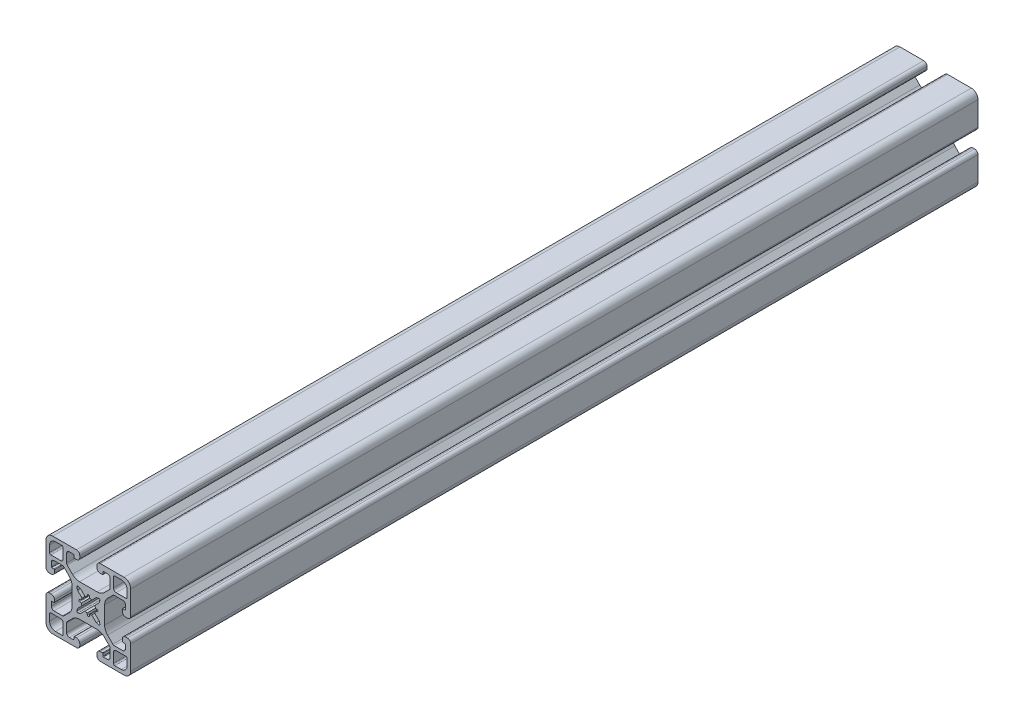
SolidWorks part; units mm, degrees
other "Extrude1"
material "6105-T5 Aluminum"
ref_plane "Front Plane" through (0, 0, 0) normal (0, 0, 1) x (1, 0, 0)
ref_plane "Top Plane" through (0, 0, 0) normal (0, 1, 0) x (1, 0, 0)
ref_plane "Right Plane" through (0, 0, 0) normal (1, 0, 0) x (0, 0, -1)
sketch "Sketch1" plane through (0, 0, 0) normal (0, 0, 1) x (1, 0, 0)
  line L0 (12.4898, -18.345) -> (15.545, -18.345)
  line L1 (11.8598, -13.1298) -> (11.8598, -17.715)
  line L2 (17.715, -11.8598) -> (13.1298, -11.8598)
  line L3 (18.345, -15.545) -> (18.345, -12.4898)
  line L4 (-18.345, -12.4898) -> (-18.345, -15.545)
  line L5 (-13.1298, -11.8598) -> (-17.715, -11.8598)
  line L6 (-11.8598, -17.715) -> (-11.8598, -13.1298)
  line L7 (-15.545, -18.345) -> (-12.4898, -18.345)
  line L8 (18.345, 12.4898) -> (18.345, 15.545)
  line L9 (13.1298, 11.8598) -> (17.715, 11.8598)
  line L10 (11.8598, 17.715) -> (11.8598, 13.1298)
  line L11 (15.545, 18.345) -> (12.4898, 18.345)
  line L12 (-12.4898, 18.345) -> (-15.545, 18.345)
  line L13 (-11.8598, 13.1298) -> (-11.8598, 17.715)
  line L14 (-17.715, 11.8598) -> (-13.1298, 11.8598)
  line L15 (-18.345, 15.545) -> (-18.345, 12.4898)
  line L16 (-5.63, 20) -> (-16.83, 20)
  line L17 (-20, 16.83) -> (-20, 5.63)
  line L18 (-18.43, 4.06) -> (-17.57, 4.06)
  line L19 (-16, 5.63) -> (-16, 6.605)
  line L20 (-16.25, 6.855) -> (-17.25, 6.855)
  line L21 (-17.5, 7.105) -> (-17.5, 9.015)
  line L22 (-16.23, 10.285) -> (-12.2162, 10.285)
  line L23 (-11.5869, 10.0243) -> (-9.0762, 7.5137)
  line L24 (-7.685, 4.1549) -> (-7.685, -4.1549)
  line L25 (-9.0762, -7.5137) -> (-11.5869, -10.0243)
  line L26 (-12.2162, -10.285) -> (-16.23, -10.285)
  line L27 (-17.5, -9.015) -> (-17.5, -7.105)
  line L28 (-17.25, -6.855) -> (-16.25, -6.855)
  line L29 (-16, -6.605) -> (-16, -5.63)
  line L30 (-17.57, -4.06) -> (-18.43, -4.06)
  line L31 (-20, -5.63) -> (-20, -16.83)
  line L32 (-16.83, -20) -> (-5.63, -20)
  line L33 (-4.06, -18.43) -> (-4.06, -17.57)
  line L34 (-5.63, -16) -> (-6.605, -16)
  line L35 (-6.855, -16.25) -> (-6.855, -17.25)
  line L36 (-7.105, -17.5) -> (-9.015, -17.5)
  line L37 (-10.285, -16.23) -> (-10.285, -12.2162)
  line L38 (-10.0243, -11.5869) -> (-7.5137, -9.0762)
  line L39 (-4.1549, -7.685) -> (4.1549, -7.685)
  line L40 (7.5137, -9.0762) -> (10.0243, -11.5869)
  line L41 (10.285, -12.2162) -> (10.285, -16.23)
  line L42 (9.015, -17.5) -> (7.105, -17.5)
  line L43 (6.855, -17.25) -> (6.855, -16.25)
  line L44 (6.605, -16) -> (5.63, -16)
  line L45 (4.06, -17.57) -> (4.06, -18.43)
  line L46 (5.63, -20) -> (16.83, -20)
  line L47 (20, -16.83) -> (20, -5.63)
  line L48 (18.43, -4.06) -> (17.57, -4.06)
  line L49 (16, -5.63) -> (16, -6.605)
  line L50 (16.25, -6.855) -> (17.25, -6.855)
  line L51 (17.5, -7.105) -> (17.5, -9.015)
  line L52 (16.23, -10.285) -> (12.2162, -10.285)
  line L53 (11.5869, -10.0243) -> (9.0762, -7.5137)
  line L54 (7.685, -4.1549) -> (7.685, 4.1549)
  line L55 (9.0762, 7.5137) -> (11.5869, 10.0243)
  line L56 (12.2162, 10.285) -> (16.23, 10.285)
  line L57 (17.5, 9.015) -> (17.5, 7.105)
  line L58 (17.25, 6.855) -> (16.25, 6.855)
  line L59 (16, 6.605) -> (16, 5.63)
  line L60 (17.57, 4.06) -> (18.43, 4.06)
  line L61 (20, 5.63) -> (20, 16.83)
  line L62 (16.83, 20) -> (5.63, 20)
  line L63 (4.06, 18.43) -> (4.06, 17.57)
  line L64 (5.63, 16) -> (6.605, 16)
  line L65 (6.855, 16.25) -> (6.855, 17.25)
  line L66 (7.105, 17.5) -> (9.015, 17.5)
  line L67 (10.285, 16.23) -> (10.285, 12.2162)
  line L68 (10.0243, 11.5869) -> (7.5137, 9.0762)
  line L69 (4.1549, 7.685) -> (-4.1549, 7.685)
  line L70 (-7.5137, 9.0762) -> (-10.0243, 11.5869)
  line L71 (-10.285, 12.2162) -> (-10.285, 16.23)
  line L72 (-9.015, 17.5) -> (-7.105, 17.5)
  line L73 (-6.855, 17.25) -> (-6.855, 16.25)
  line L74 (-6.605, 16) -> (-5.63, 16)
  line L75 (-4.06, 17.57) -> (-4.06, 18.43)
  line L76 (-4.8481, -5.4393) -> (-3.712, -5.1263)
  line L77 (-3.712, -5.1263) -> (-1.5907, -3.0049)
  line L78 (-0.625, -3.3421) -> (-0.4923, -4.0876)
  line L79 (0.4923, -4.0876) -> (0.625, -3.3421)
  line L80 (1.5907, -3.0049) -> (3.712, -5.1263)
  line L81 (3.712, -5.1263) -> (4.8481, -5.4393)
  line L82 (5.4393, -4.8481) -> (5.1263, -3.712)
  line L83 (5.1263, -3.712) -> (3.0049, -1.5907)
  line L84 (3.3421, -0.625) -> (4.0876, -0.4923)
  line L85 (4.0876, 0.4923) -> (3.3421, 0.625)
  line L86 (3.0049, 1.5907) -> (5.1263, 3.712)
  line L87 (5.1263, 3.712) -> (5.4393, 4.8481)
  line L88 (4.8481, 5.4393) -> (3.712, 5.1263)
  line L89 (3.712, 5.1263) -> (1.5907, 3.0049)
  line L90 (0.625, 3.3421) -> (0.4923, 4.0876)
  line L91 (-0.4923, 4.0876) -> (-0.625, 3.3421)
  line L92 (-1.5907, 3.0049) -> (-3.712, 5.1263)
  line L93 (-3.712, 5.1263) -> (-4.8481, 5.4393)
  line L94 (-5.4393, 4.8481) -> (-5.1263, 3.712)
  line L95 (-5.1263, 3.712) -> (-3.0049, 1.5907)
  line L96 (-3.3421, 0.625) -> (-4.0876, 0.4923)
  line L97 (-4.0876, -0.4923) -> (-3.3421, -0.625)
  line L98 (-3.0049, -1.5907) -> (-5.1263, -3.712)
  line L99 (-5.1263, -3.712) -> (-5.4393, -4.8481)
  arc A0 (15.545, -18.345) -> (18.345, -15.545) centre (15.545, -15.545) ccw
  arc A1 (11.8598, -17.715) -> (12.4898, -18.345) centre (12.4898, -17.715) ccw
  arc A2 (13.1298, -11.8598) -> (11.8598, -13.1298) centre (13.1298, -13.1298) ccw
  arc A3 (18.345, -12.4898) -> (17.715, -11.8598) centre (17.715, -12.4898) ccw
  arc A4 (-18.345, -15.545) -> (-15.545, -18.345) centre (-15.545, -15.545) ccw
  arc A5 (-17.715, -11.8598) -> (-18.345, -12.4898) centre (-17.715, -12.4898) ccw
  arc A6 (-11.8598, -13.1298) -> (-13.1298, -11.8598) centre (-13.1298, -13.1298) ccw
  arc A7 (-12.4898, -18.345) -> (-11.8598, -17.715) centre (-12.4898, -17.715) ccw
  arc A8 (18.345, 15.545) -> (15.545, 18.345) centre (15.545, 15.545) ccw
  arc A9 (17.715, 11.8598) -> (18.345, 12.4898) centre (17.715, 12.4898) ccw
  arc A10 (11.8598, 13.1298) -> (13.1298, 11.8598) centre (13.1298, 13.1298) ccw
  arc A11 (12.4898, 18.345) -> (11.8598, 17.715) centre (12.4898, 17.715) ccw
  arc A12 (-15.545, 18.345) -> (-18.345, 15.545) centre (-15.545, 15.545) ccw
  arc A13 (-11.8598, 17.715) -> (-12.4898, 18.345) centre (-12.4898, 17.715) ccw
  arc A14 (-13.1298, 11.8598) -> (-11.8598, 13.1298) centre (-13.1298, 13.1298) ccw
  arc A15 (-18.345, 12.4898) -> (-17.715, 11.8598) centre (-17.715, 12.4898) ccw
  arc A16 (-4.06, 18.43) -> (-5.63, 20) centre (-5.63, 18.43) ccw
  arc A17 (-16.83, 20) -> (-20, 16.83) centre (-16.83, 16.83) ccw
  arc A18 (-20, 5.63) -> (-18.43, 4.06) centre (-18.43, 5.63) ccw
  arc A19 (-17.57, 4.06) -> (-16, 5.63) centre (-17.57, 5.63) ccw
  arc A20 (-16, 6.605) -> (-16.25, 6.855) centre (-16.25, 6.605) ccw
  arc A21 (-17.5, 7.105) -> (-17.25, 6.855) centre (-17.25, 7.105) ccw
  arc A22 (-16.23, 10.285) -> (-17.5, 9.015) centre (-16.23, 9.015) ccw
  arc A23 (-11.5869, 10.0243) -> (-12.2162, 10.285) centre (-12.2162, 9.395) ccw
  arc A24 (-7.685, 4.1549) -> (-9.0762, 7.5137) centre (-12.435, 4.1549) ccw
  arc A25 (-9.0762, -7.5137) -> (-7.685, -4.1549) centre (-12.435, -4.1549) ccw
  arc A26 (-12.2162, -10.285) -> (-11.5869, -10.0243) centre (-12.2162, -9.395) ccw
  arc A27 (-17.5, -9.015) -> (-16.23, -10.285) centre (-16.23, -9.015) ccw
  arc A28 (-17.25, -6.855) -> (-17.5, -7.105) centre (-17.25, -7.105) ccw
  arc A29 (-16.25, -6.855) -> (-16, -6.605) centre (-16.25, -6.605) ccw
  arc A30 (-16, -5.63) -> (-17.57, -4.06) centre (-17.57, -5.63) ccw
  arc A31 (-18.43, -4.06) -> (-20, -5.63) centre (-18.43, -5.63) ccw
  arc A32 (-20, -16.83) -> (-16.83, -20) centre (-16.83, -16.83) ccw
  arc A33 (-5.63, -20) -> (-4.06, -18.43) centre (-5.63, -18.43) ccw
  arc A34 (-4.06, -17.57) -> (-5.63, -16) centre (-5.63, -17.57) ccw
  arc A35 (-6.605, -16) -> (-6.855, -16.25) centre (-6.605, -16.25) ccw
  arc A36 (-7.105, -17.5) -> (-6.855, -17.25) centre (-7.105, -17.25) ccw
  arc A37 (-10.285, -16.23) -> (-9.015, -17.5) centre (-9.015, -16.23) ccw
  arc A38 (-10.0243, -11.5869) -> (-10.285, -12.2162) centre (-9.395, -12.2162) ccw
  arc A39 (-4.1549, -7.685) -> (-7.5137, -9.0762) centre (-4.1549, -12.435) ccw
  arc A40 (7.5137, -9.0762) -> (4.1549, -7.685) centre (4.1549, -12.435) ccw
  arc A41 (10.285, -12.2162) -> (10.0243, -11.5869) centre (9.395, -12.2162) ccw
  arc A42 (9.015, -17.5) -> (10.285, -16.23) centre (9.015, -16.23) ccw
  arc A43 (6.855, -17.25) -> (7.105, -17.5) centre (7.105, -17.25) ccw
  arc A44 (6.855, -16.25) -> (6.605, -16) centre (6.605, -16.25) ccw
  arc A45 (5.63, -16) -> (4.06, -17.57) centre (5.63, -17.57) ccw
  arc A46 (4.06, -18.43) -> (5.63, -20) centre (5.63, -18.43) ccw
  arc A47 (16.83, -20) -> (20, -16.83) centre (16.83, -16.83) ccw
  arc A48 (20, -5.63) -> (18.43, -4.06) centre (18.43, -5.63) ccw
  arc A49 (17.57, -4.06) -> (16, -5.63) centre (17.57, -5.63) ccw
  arc A50 (16, -6.605) -> (16.25, -6.855) centre (16.25, -6.605) ccw
  arc A51 (17.5, -7.105) -> (17.25, -6.855) centre (17.25, -7.105) ccw
  arc A52 (16.23, -10.285) -> (17.5, -9.015) centre (16.23, -9.015) ccw
  arc A53 (11.5869, -10.0243) -> (12.2162, -10.285) centre (12.2162, -9.395) ccw
  arc A54 (7.685, -4.1549) -> (9.0762, -7.5137) centre (12.435, -4.1549) ccw
  arc A55 (9.0762, 7.5137) -> (7.685, 4.1549) centre (12.435, 4.1549) ccw
  arc A56 (12.2162, 10.285) -> (11.5869, 10.0243) centre (12.2162, 9.395) ccw
  arc A57 (17.5, 9.015) -> (16.23, 10.285) centre (16.23, 9.015) ccw
  arc A58 (17.25, 6.855) -> (17.5, 7.105) centre (17.25, 7.105) ccw
  arc A59 (16.25, 6.855) -> (16, 6.605) centre (16.25, 6.605) ccw
  arc A60 (16, 5.63) -> (17.57, 4.06) centre (17.57, 5.63) ccw
  arc A61 (18.43, 4.06) -> (20, 5.63) centre (18.43, 5.63) ccw
  arc A62 (20, 16.83) -> (16.83, 20) centre (16.83, 16.83) ccw
  arc A63 (5.63, 20) -> (4.06, 18.43) centre (5.63, 18.43) ccw
  arc A64 (4.06, 17.57) -> (5.63, 16) centre (5.63, 17.57) ccw
  arc A65 (6.605, 16) -> (6.855, 16.25) centre (6.605, 16.25) ccw
  arc A66 (7.105, 17.5) -> (6.855, 17.25) centre (7.105, 17.25) ccw
  arc A67 (10.285, 16.23) -> (9.015, 17.5) centre (9.015, 16.23) ccw
  arc A68 (10.0243, 11.5869) -> (10.285, 12.2162) centre (9.395, 12.2162) ccw
  arc A69 (4.1549, 7.685) -> (7.5137, 9.0762) centre (4.1549, 12.435) ccw
  arc A70 (-7.5137, 9.0762) -> (-4.1549, 7.685) centre (-4.1549, 12.435) ccw
  arc A71 (-10.285, 12.2162) -> (-10.0243, 11.5869) centre (-9.395, 12.2162) ccw
  arc A72 (-9.015, 17.5) -> (-10.285, 16.23) centre (-9.015, 16.23) ccw
  arc A73 (-6.855, 17.25) -> (-7.105, 17.5) centre (-7.105, 17.25) ccw
  arc A74 (-6.855, 16.25) -> (-6.605, 16) centre (-6.605, 16.25) ccw
  arc A75 (-5.63, 16) -> (-4.06, 17.57) centre (-5.63, 17.57) ccw
  arc A76 (-1.5907, -3.0049) -> (-0.625, -3.3421) centre (0, 0) ccw
  arc A77 (-0.4923, -4.0876) -> (0.4923, -4.0876) centre (0, -4) ccw
  arc A78 (0.625, -3.3421) -> (1.5907, -3.0049) centre (0, 0) ccw
  arc A79 (4.8481, -5.4393) -> (5.4393, -4.8481) centre (4.9497, -4.9497) ccw
  arc A80 (3.0049, -1.5907) -> (3.3421, -0.625) centre (0, 0) ccw
  arc A81 (4.0876, -0.4923) -> (4.0876, 0.4923) centre (4, 0) ccw
  arc A82 (3.3421, 0.625) -> (3.0049, 1.5907) centre (0, 0) ccw
  arc A83 (5.4393, 4.8481) -> (4.8481, 5.4393) centre (4.9497, 4.9497) ccw
  arc A84 (1.5907, 3.0049) -> (0.625, 3.3421) centre (0, 0) ccw
  arc A85 (0.4923, 4.0876) -> (-0.4923, 4.0876) centre (0, 4) ccw
  arc A86 (-0.625, 3.3421) -> (-1.5907, 3.0049) centre (0, 0) ccw
  arc A87 (-4.8481, 5.4393) -> (-5.4393, 4.8481) centre (-4.9497, 4.9497) ccw
  arc A88 (-3.0049, 1.5907) -> (-3.3421, 0.625) centre (0, 0) ccw
  arc A89 (-4.0876, 0.4923) -> (-4.0876, -0.4923) centre (-4, 0) ccw
  arc A90 (-3.3421, -0.625) -> (-3.0049, -1.5907) centre (0, 0) ccw
  arc A91 (-5.4393, -4.8481) -> (-4.8481, -5.4393) centre (-4.9497, -4.9497) ccw
extrude "Extrude1" add sketch "Sketch1" against normal blind 400
equation "\"0.400.00mm\"=1400"
